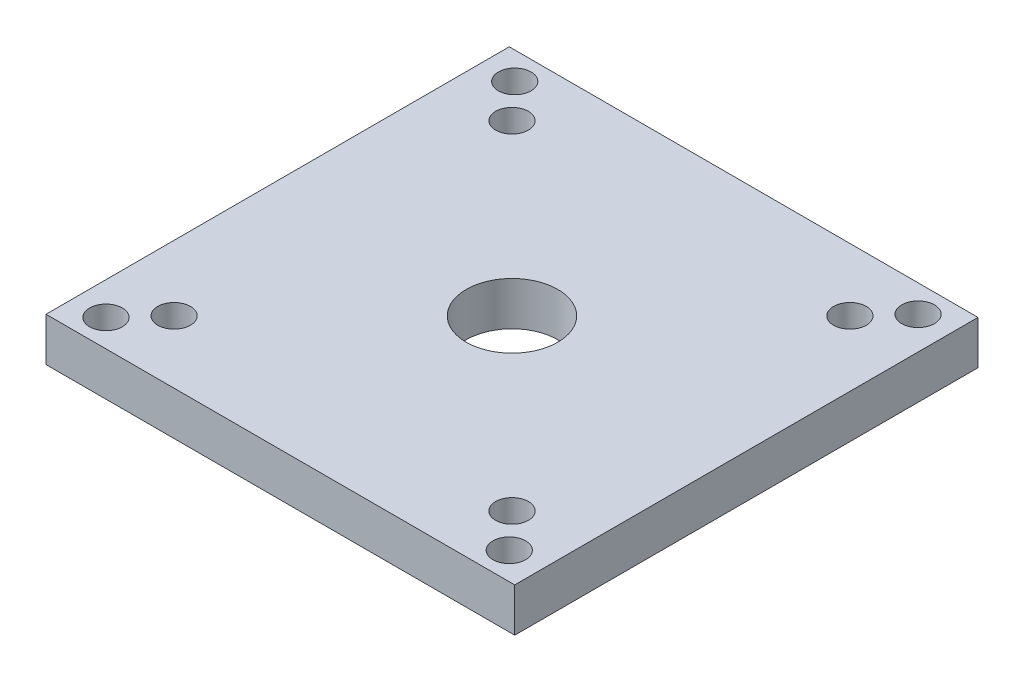
SolidWorks part; units mm, degrees
ref_plane "Спереди" through (0, 0, 0) normal (0, 0, 1) x (1, 0, 0)
ref_plane "Сверху" through (0, 0, 0) normal (0, 1, 0) x (1, 0, 0)
ref_plane "Справа" through (0, 0, 0) normal (1, 0, 0) x (0, 0, -1)
sketch "Эскиз1" plane through (0, 0, 0) normal (0, 1, 0) x (1, 0, 0)
  line L1 (-36.5645, 28.9732) -> (6.4355, 28.9732)
  line L2 (-36.5645, 28.9732) -> (-36.5645, -13.5268)
  line L3 (-36.5645, -13.5268) -> (6.4355, -13.5268)
  line L4 (6.4355, 28.9732) -> (6.4355, -13.5268)
  dimension "D1" = 43
  dimension "D2" = 42.5
extrude "Бобышка-Вытянуть1" add sketch "Эскиз1" along normal blind 4
sketch "Эскиз2" plane through (0, 0, 0) normal (0, -1, 0) x (1, 0, 0)
  circle A0 centre (-33.5645, 11.0268) radius 1.5
  circle A1 centre (3.4355, 11.0268) radius 1.5
  circle A2 centre (-33.5645, -26.4732) radius 1.5
  circle A3 centre (3.4355, -26.4732) radius 1.5
extrude "Вырез-Вытянуть1" cut sketch "Эскиз2" against normal blind 10
sketch "Эскиз3" plane through (0, 0, 0) normal (0, -1, 0) x (1, 0, 0)
  circle A0 centre (-30.5645, 7.7768) radius 1.5
  circle A1 centre (-30.5645, -23.2232) radius 1.5
  circle A2 centre (0.4355, 7.7768) radius 1.5
  circle A3 centre (0.4355, -23.2232) radius 1.5
extrude "Вырез-Вытянуть2" cut sketch "Эскиз3" against normal blind 10
sketch "Эскиз4" plane through (0, 4, 0) normal (0, 1, 0) x (1, 0, 0)
  line L0 (-15.0645, 28.9732) -> (-15.0645, -13.5268) construction
  line L1 (6.4355, 28.9732) -> (-36.5645, 28.9732) construction
  line L2 (-36.5645, -13.5268) -> (6.4355, -13.5268) construction
  line L3 (-15.0645, -13.5268) -> (6.4355, 7.7232) construction
  line L4 (6.4355, -13.5268) -> (6.4355, 28.9732) construction
  line L5 (6.4355, 7.7232) -> (-36.5645, 7.7232) construction
  line L6 (-36.5645, 28.9732) -> (-36.5645, -13.5268) construction
  circle A0 centre (-15.0645, 7.7232) radius 4.2
  dimension "D1" = 8.4
extrude "Вырез-Вытянуть3" cut sketch "Эскиз4" against normal blind 4
